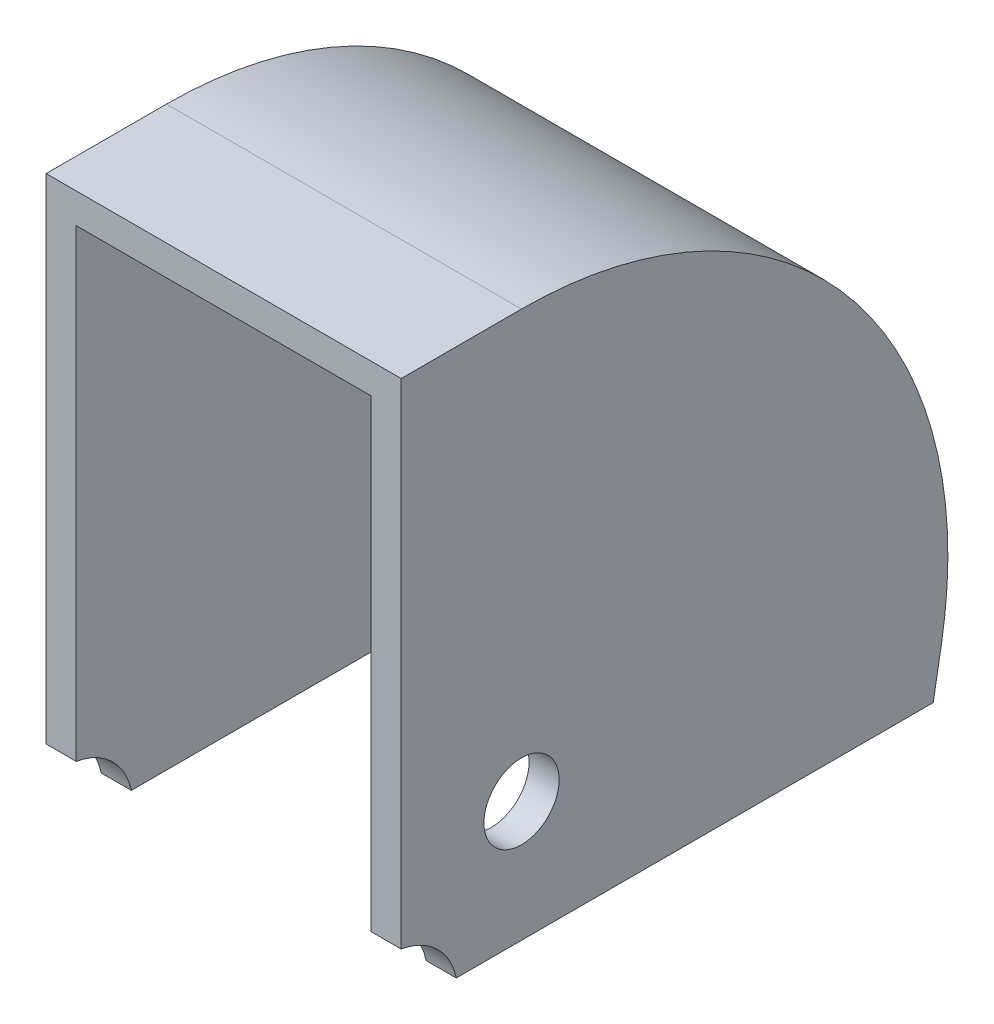
SolidWorks part; units mm, degrees
ref_plane "Front Plane" through (0, 0, 0) normal (0, 0, 1) x (1, 0, 0)
ref_plane "Top Plane" through (0, 0, 0) normal (0, 1, 0) x (1, 0, 0)
ref_plane "Right Plane" through (0, 0, 0) normal (1, 0, 0) x (0, 0, -1)
sketch "Sketch1" plane through (0, 0, 0) normal (1, 0, 0) x (0, 0, -1)
  line L0 (-8, -4.5) -> (-8, 28.3351)
  line L1 (-4.3357, -8) -> (27.3616, -8)
  line L2 (0, 0) -> (-8, 0) construction
  line L3 (0, -7) -> (0, -8) construction
  line L4 (0, 0) -> (0, 28.3351) construction
  line L5 (-8, 28.3351) -> (0, 28.3351)
  line L6 (27.3616, -8) -> (27.9046, -4.9203)
  line L7 (-5.6284, -5.6852) -> (-4.9248, -4.9746) construction
  circle A0 centre (0, 0) radius 7 construction
  arc A1 (-8, -4.5) -> (-4.3357, -8) centre (-8.7365, -8.9393) cw
  arc A2 (0, 28.3351) -> (27.9046, -4.9203) centre (0, 0) cw
  circle A3 centre (0, 0) radius 10 construction
  dimension "D1" = 14
  dimension "D4" = 20
  dimension "D7" = 4.5
  dimension "D2" = 1
  dimension "D3" = 8
  dimension "D6" = 4.5
  dimension "D8" = 100
  dimension "D9" = 1
  dimension "D5" = 28.3351
extrude "Boss-Extrude1" add sketch "Sketch1" along normal blind 2
sketch "Sketch6" plane through (0, 0, 0) normal (-1, 0, 0) x (0, 0, 1)
  line L0 (8, 26.3351) -> (0, 26.3351)
  line L1 (8, 28.3351) -> (8, -4.5) construction
  line L2 (-25.3308, -8) -> (-25.935, -4.573)
  line L3 (4.3357, -8) -> (-27.3616, -8) construction
  line L4 (-27.3616, -8) -> (-27.9046, -4.9203) construction
  line L7 (0, 28.3351) -> (8, 28.3351) construction
  line L8 (-25.3308, -8) -> (-27.3616, -8)
  line L9 (-27.3616, -8) -> (-27.9046, -4.9203)
  line L10 (8, 26.3351) -> (8, 28.3351)
  line L11 (8, 28.3351) -> (0, 28.3351)
  arc A0 (0, 26.3351) -> (-25.935, -4.573) centre (0, 0) ccw
  arc A1 (0, 28.3351) -> (-27.9046, -4.9203) centre (0, 0) ccw
  dimension "D1" = 2
  dimension "D2" = 2
extrude "Boss-Extrude2" add sketch "Sketch6" along normal blind 9.7967
mirror "Mirror1" about plane through (-9.7967, 0, 0) normal (-1, 0, 0) of bodies 106
sketch "Sketch4" plane through (2, 0, 0) normal (1, 0, 0) x (0, 0, -1)
  circle A0 centre (0, 0) radius 2.5
  dimension "D1" = 5
extrude "Cut-Extrude5" cut sketch "Sketch4" against normal blind 13
equation "\"LA_height\"=28.33511482"
equation "\"partial_pulley_height\"= \"LA_height\""
equation "\"D5@Sketch1\"=\"partial_pulley_height\""
equation "\"LA_width\"=19.59343046"
equation "\"pulley_width\"= \"LA_width\" / 2"
equation "\"D1@Boss-Extrude2\"=\"pulley_width\""
equation "\"LA_length\"=104.84505691"
equation "\"radius_pin\"=9.79671523"
